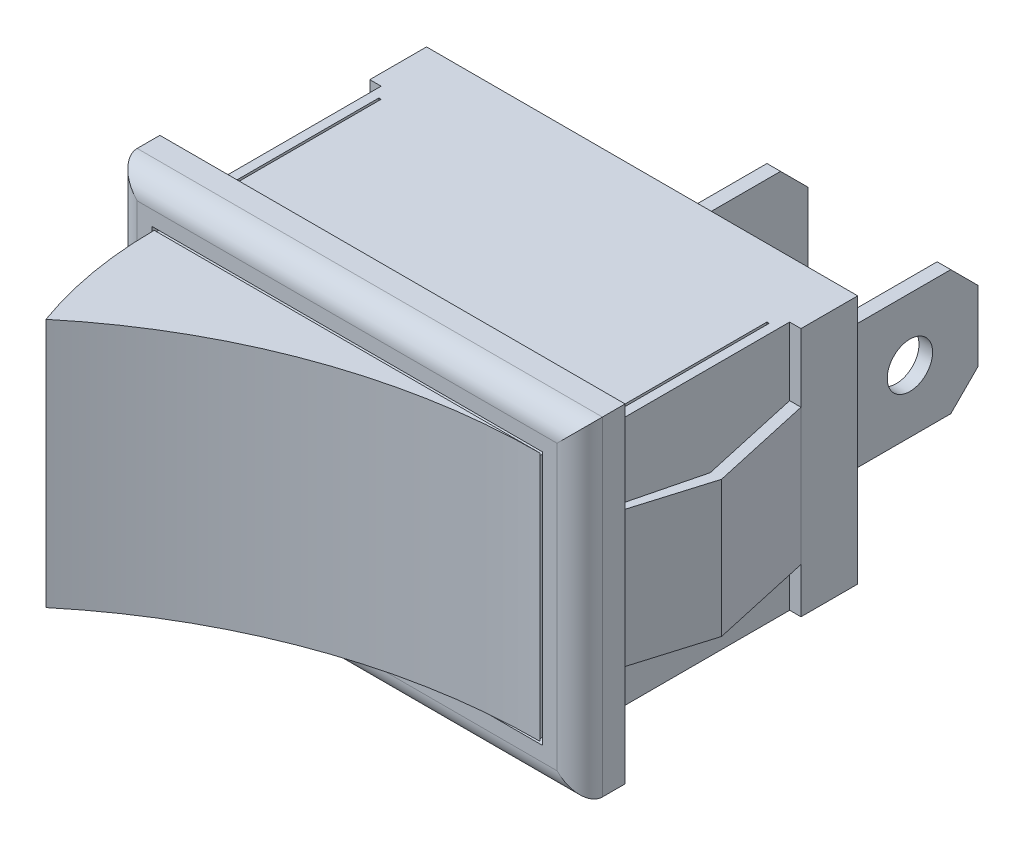
SolidWorks part; units mm, degrees
ref_plane "Front" through (0, 0, 0) normal (0, 0, 1) x (1, 0, 0)
ref_plane "Top" through (0, 0, 0) normal (0, 1, 0) x (1, 0, 0)
ref_plane "Right" through (0, 0, 0) normal (1, 0, 0) x (0, 0, -1)
sketch "草图1" plane through (0, 0, 0) normal (0, 0, 1) x (1, 0, 0)
  line L1 (0, 0) -> (20.5, 0)
  line L2 (0, 0) -> (0, 14.5)
  line L3 (0, 14.5) -> (20.5, 14.5)
  line L4 (20.5, 0) -> (20.5, 14.5)
  dimension "D1" = 20.5
  dimension "D2" = 14.5
extrude "凸台-拉伸1" add sketch "草图1" along normal blind 2
fillet "圆角1" radius 1 4 edges at (10.25, 14.5, 2) (20.5, 7.25, 2) (10.25, 0, 2) (0, 7.25, 2)
sketch "草图2" plane through (0, 0, 0) normal (0, 0, -1) x (-1, 0, 0)
  line L0 (-20.5, 0) -> (-20.5, 14.5) construction
  line L1 (-1.25, 1.75) -> (-19.25, 1.75)
  line L2 (-1.25, 1.75) -> (-1.25, 12.75)
  line L3 (-1.25, 12.75) -> (-19.25, 12.75)
  line L4 (-19.25, 1.75) -> (-19.25, 12.75)
  line L6 (0, 0) -> (-20.5, 0) construction
  dimension "D1" = 18
  dimension "D2" = 11
  dimension "D3" = 1.25
  dimension "D4" = 1.75
extrude "凸台-拉伸2" add sketch "草图2" along normal blind 11
sketch "草图3" plane through (19.25, 0, 0) normal (1, 0, 0) x (0, 0, -1)
  line L0 (11, 12.75) -> (0, 12.75) construction
  line L1 (11, 1.75) -> (8.5, 1.75)
  line L2 (11, 1.75) -> (11, 12.75)
  line L3 (11, 12.75) -> (8.5, 12.75)
  line L4 (8.5, 1.75) -> (8.5, 12.75)
  dimension "D1" = 2.5
extrude "凸台-拉伸3" add sketch "草图3" along normal blind 0.5
sketch "草图4" plane through (1.25, 0, 0) normal (-1, 0, 0) x (0, 0, 1)
  line L0 (-11, 12.75) -> (0, 12.75) construction
  line L1 (-11, 1.75) -> (-8.5, 1.75)
  line L2 (-11, 1.75) -> (-11, 12.75)
  line L3 (-11, 12.75) -> (-8.5, 12.75)
  line L4 (-8.5, 1.75) -> (-8.5, 12.75)
  dimension "D1" = 2.5
extrude "凸台-拉伸4" add sketch "草图4" along normal blind 0.5
sketch "草图5" plane through (0, 12.75, 0) normal (0, 1, 0) x (1, 0, 0)
  line L0 (1.25, 0) -> (19.25, 0) construction
  circle A0 centre (10.25, 0.5) radius 0.3
  dimension "D1" = 0.5
extrude "切除-拉伸1" cut sketch "草图5" against normal through all
sketch "草图6" plane through (0, 0, -11) normal (0, 0, -1) x (-1, 0, 0)
  line L0 (-19.75, 1.75) -> (-19.75, 12.75) construction
  line L1 (-18.75, 9.25) -> (-18.15, 9.25)
  line L2 (-18.75, 9.25) -> (-18.75, 5.25)
  line L3 (-18.75, 5.25) -> (-18.15, 5.25)
  line L4 (-18.15, 9.25) -> (-18.15, 5.25)
  line L5 (-20.5, 0) -> (-20.5, 14.5) construction
  line L6 (-0.75, 12.75) -> (-0.75, 1.75) construction
  line L7 (-17.35, 9.25) -> (-16.75, 9.25)
  line L8 (-17.35, 9.25) -> (-17.35, 5.25)
  line L9 (-17.35, 5.25) -> (-16.75, 5.25)
  line L10 (-16.75, 9.25) -> (-16.75, 5.25)
  line L11 (-11.25, 9.25) -> (-10.65, 9.25)
  line L12 (-11.25, 9.25) -> (-11.25, 5.25)
  line L13 (-11.25, 5.25) -> (-10.65, 5.25)
  line L14 (-10.65, 9.25) -> (-10.65, 5.25)
  line L15 (-9.85, 9.25) -> (-9.25, 9.25)
  line L16 (-9.85, 9.25) -> (-9.85, 5.25)
  line L17 (-9.85, 5.25) -> (-9.25, 5.25)
  line L18 (-9.25, 9.25) -> (-9.25, 5.25)
  line L19 (-3.75, 9.25) -> (-3.15, 9.25)
  line L20 (-3.75, 9.25) -> (-3.75, 5.25)
  line L21 (-3.75, 5.25) -> (-3.15, 5.25)
  line L22 (-3.15, 9.25) -> (-3.15, 5.25)
  line L23 (-2.35, 9.25) -> (-1.75, 9.25)
  line L24 (-2.35, 9.25) -> (-2.35, 5.25)
  line L25 (-2.35, 5.25) -> (-1.75, 5.25)
  line L26 (-1.75, 9.25) -> (-1.75, 5.25)
  line L27 (-1.25, 12.75) -> (-19.25, 12.75) construction
  point P6 (-18.75, 7.25)
  point P9 (-20.5, 7.25)
  point P34 (-10.25, 12.75)
  dimension "D1" = 4
  dimension "D2" = 0.6
  dimension "D3" = 1
  dimension "D4" = 0
  dimension "D5" = 0.6
  dimension "D6" = 0.8
  dimension "D7" = 0.6
  dimension "D8" = 0.6
  dimension "D9" = 0.6
  dimension "D10" = 0.6
  dimension "D11" = 0.8
  dimension "D12" = 0.8
  dimension "D13" = 1
  dimension "D14" = 0.4
extrude "凸台-拉伸5" add sketch "草图6" along normal blind 0.5
sketch "草图7" plane through (0, 0, -11) normal (0, 0, -1) x (-1, 0, 0)
  line L0 (-18.15, 9.25) -> (-18.75, 9.25) construction
  line L1 (-18.15, 4.25) -> (-17.332, 4.25)
  line L2 (-18.15, 4.25) -> (-18.15, 10.25)
  line L3 (-18.15, 10.25) -> (-17.332, 10.25)
  line L4 (-17.332, 4.25) -> (-17.332, 10.25)
  line L6 (-10.65, 4.25) -> (-9.85, 4.25)
  line L7 (-10.65, 4.25) -> (-10.65, 10.25)
  line L8 (-10.65, 10.25) -> (-9.85, 10.25)
  line L9 (-9.85, 4.25) -> (-9.85, 10.25)
  line L10 (-3.15, 10.25) -> (-2.35, 10.25)
  line L11 (-3.15, 10.25) -> (-3.15, 4.25)
  line L12 (-3.15, 4.25) -> (-2.35, 4.25)
  line L13 (-2.35, 10.25) -> (-2.35, 4.25)
  dimension "D1" = 6
  dimension "D2" = 1
extrude "切除-拉伸2" cut sketch "草图7" against normal blind 4
sketch "草图8" plane through (0, 0, -7) normal (0, 0, -1) x (-1, 0, 0)
  line L0 (-18.15, 10.25) -> (-18.15, 9.25) construction
  line L1 (-18.05, 10) -> (-17.45, 10)
  line L2 (-18.05, 10) -> (-18.05, 4.5)
  line L3 (-18.05, 4.5) -> (-17.45, 4.5)
  line L4 (-17.45, 10) -> (-17.45, 4.5)
  line L5 (-17.332, 10.25) -> (-18.15, 10.25) construction
  line L6 (-10.65, 10.25) -> (-10.65, 4.25) construction
  line L7 (-10.55, 10) -> (-9.95, 10)
  line L8 (-10.55, 10) -> (-10.55, 4.5)
  line L9 (-10.55, 4.5) -> (-9.95, 4.5)
  line L10 (-9.95, 10) -> (-9.95, 4.5)
  dimension "D1" = 0.6
  dimension "D2" = 0.1
  dimension "D3" = 5.5
  dimension "D4" = 0.25
  dimension "D5" = 0.6
  dimension "D6" = 0.1
extrude "凸台-拉伸6" add sketch "草图8" along normal blind 11
chamfer "倒角1" distance 1.2 angle 45 4 edges at (10.25, 4.5, -18) (10.25, 10, -18) (17.75, 4.5, -18) (17.75, 10, -18)
sketch "草图9" plane through (18.05, 0, 0) normal (1, 0, 0) x (0, 0, -1)
  line L0 (18, 8.8) -> (18, 5.7) construction
  circle A0 centre (15, 7.25) radius 1
  dimension "D1" = 3
extrude "切除-拉伸3" cut sketch "草图9" against normal through all
ref_plane "基准面1" through (0, 3.75, 0) normal (0, -1, 0) x (-1, 0, 0)
sketch "草图10" plane through (0, 3.75, 0) normal (0, -1, 0) x (-1, 0, 0)
  line L0 (-19.25, 0) -> (-19.55, 0)
  line L1 (0, 0) -> (-20.5, 0) construction
  line L2 (-19.55, 0) -> (-20.75, 4)
  line L3 (-20.75, 4) -> (-19.75, 8.5)
  line L4 (-19.75, 8.5) -> (-19.25, 8.5)
  line L5 (-19.25, 8.5) -> (-20.25, 4)
  line L6 (-20.25, 4) -> (-19.25, 0)
  line L7 (-19.25, 8.5) -> (-19.25, 0) construction
  line L8 (-1.25, 0) -> (-0.95, 0)
  line L9 (-0.95, 0) -> (0.25, 4)
  line L10 (0.25, 4) -> (-0.75, 8.5)
  line L11 (-0.75, 8.5) -> (-1.25, 8.5)
  line L12 (-1.25, 8.5) -> (-0.25, 4)
  line L13 (-0.25, 4) -> (-1.25, 0)
  line L14 (-1.25, 8.5) -> (-1.25, 0) construction
  dimension "D1" = 1
  dimension "D2" = 4
  dimension "D3" = 4
  dimension "D4" = 0.3
  dimension "D5" = 4
  dimension "D6" = 4
  dimension "D7" = 0.3
  dimension "D8" = 1
extrude "凸台-拉伸7" add sketch "草图10" against normal blind 6
sketch "草图11" plane through (0, 1.75, 0) normal (0, -1, 0) x (1, 0, 0)
  line L0 (1, 2) -> (19.5, 2) construction
  line L1 (19.25, -8.5) -> (19.25, 0) construction
  line L2 (18.75, 2) -> (1.75, 2)
  arc A0 (2.7628, 7.78) -> (1.75, 2) centre (18.75, 2) ccw
  arc A1 (2.7628, 7.78) -> (18.75, 2) centre (18.75, 27) ccw
  dimension "D1" = 0.5
  dimension "D2" = 34
extrude "凸台-拉伸8" add sketch "草图11" against normal blind 11
sketch "草图12" plane through (0, 0, 2) normal (0, 0, 1) x (1, 0, 0)
  line L1 (1.75, 12.75) -> (18.75, 12.75)
  line L2 (1.75, 12.75) -> (1.75, 1.75)
  line L3 (1.75, 1.75) -> (18.75, 1.75)
  line L4 (18.75, 12.75) -> (18.75, 1.75)
  line L5 (18.85, 1.65) -> (1.65, 1.65)
  line L6 (18.85, 1.65) -> (18.85, 12.85)
  line L7 (18.85, 12.85) -> (1.65, 12.85)
  line L8 (1.65, 1.65) -> (1.65, 12.85)
  dimension "D1" = 0.1
  dimension "D2" = 0.1
  dimension "D3" = 0.1
  dimension "D4" = 0.1
extrude "切除-拉伸4" cut sketch "草图12" against normal blind 10
sketch "草图13" plane through (0, 0, 2) normal (0, 0, 1) x (1, 0, 0)
  line L0 (18.75, 12.75) -> (18.75, 1.75) construction
  line L1 (1.75, 1.75) -> (18.75, 1.75)
  line L2 (1.75, 1.75) -> (1.75, 1.85)
  line L3 (1.75, 1.85) -> (18.75, 1.85)
  line L4 (18.75, 1.75) -> (18.75, 1.85)
  line L6 (18.75, 12.75) -> (1.75, 12.75)
  line L7 (18.75, 12.75) -> (18.75, 12.65)
  line L8 (18.75, 12.65) -> (1.75, 12.65)
  line L9 (1.75, 12.75) -> (1.75, 12.65)
  dimension "D1" = 0.1
  dimension "D2" = 0.1
extrude "切除-拉伸5" cut sketch "草图13" against normal blind 1
